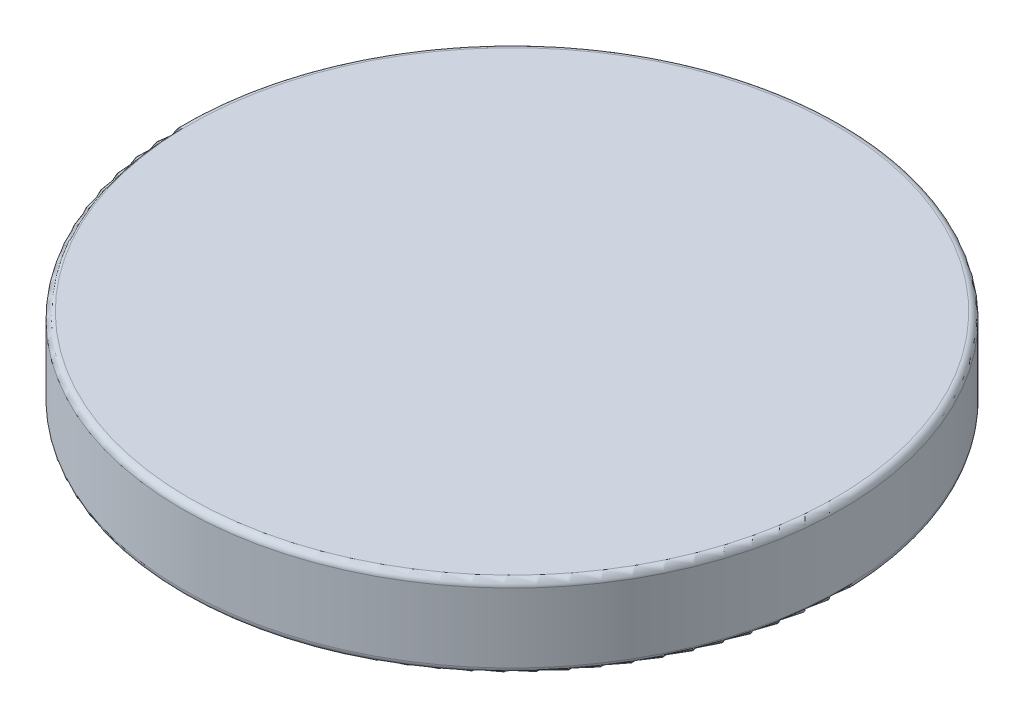
SolidWorks part; units mm, degrees
ref_plane "Front Plane" through (0, 0, 0) normal (0, 0, 1) x (1, 0, 0)
ref_plane "Top Plane" through (0, 0, 0) normal (0, 1, 0) x (1, 0, 0)
ref_plane "Right Plane" through (0, 0, 0) normal (1, 0, 0) x (0, 0, -1)
sketch "Sketch2" plane through (0, 0, 0) normal (0, 1, 0) x (1, 0, 0)
  circle A0 centre (0, 1.6609) radius 12.7
extrude "Boss-Extrude1" add sketch "Sketch2" along normal blind 3.175
fillet "Fillet1" radius 0.254 2 edges at (0, 0, 11.0391) (0, 3.175, 11.0391)
